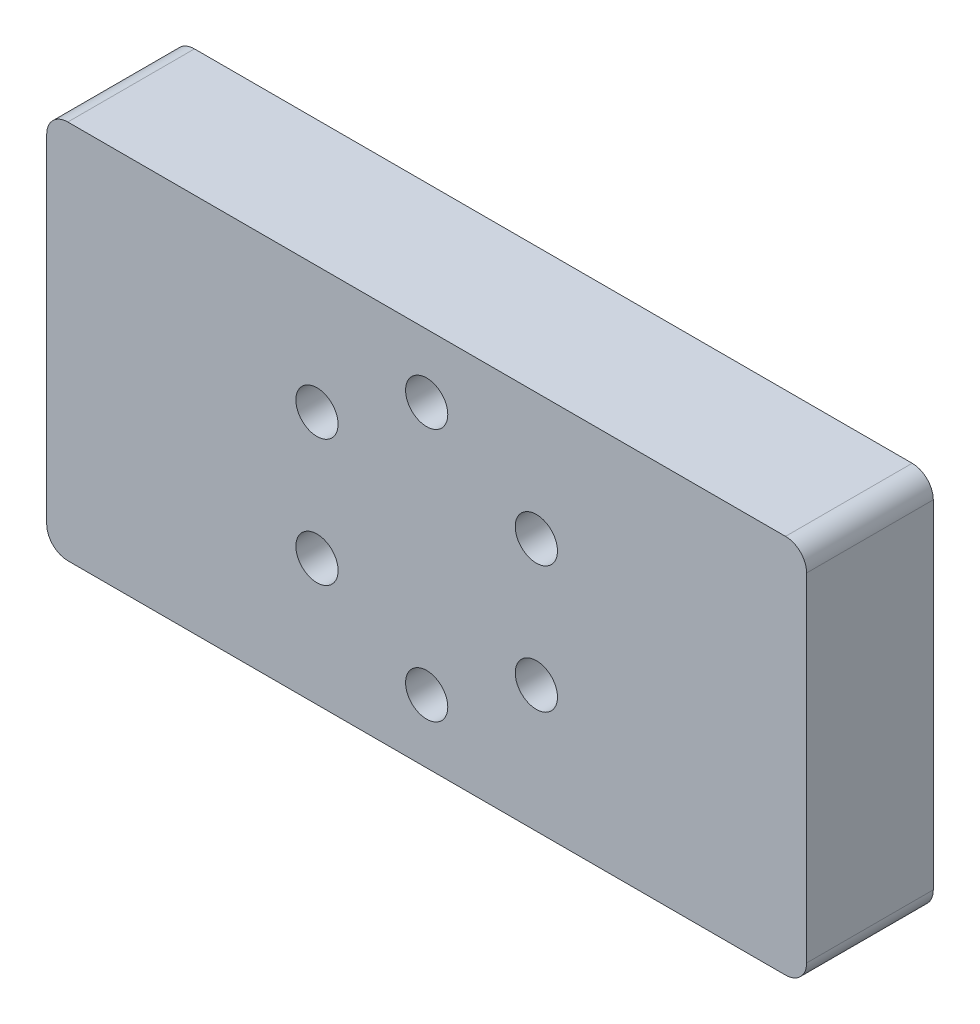
SolidWorks part; units mm, degrees
ref_plane "Plano frontal" through (0, 0, 0) normal (0, 0, 1) x (1, 0, 0)
ref_plane "Plano superior" through (0, 0, 0) normal (0, 1, 0) x (1, 0, 0)
ref_plane "Plano direito" through (0, 0, 0) normal (1, 0, 0) x (0, 0, -1)
sketch "Esboço1" plane through (0, 0, 0) normal (0, 0, 1) x (1, 0, 0)
  line L1 (-85, -45) -> (85, -45)
  line L2 (-90, -40) -> (-90, 40)
  line L3 (-85, 45) -> (85, 45)
  line L4 (90, -40) -> (90, 40)
  line L5 (-90, -45) -> (90, 45) construction
  line L6 (-90, 45) -> (90, -45) construction
  arc A0 (85, 45) -> (90, 40) centre (85, 40) cw
  arc A1 (85, -45) -> (90, -40) centre (85, -40) ccw
  arc A2 (-85, -45) -> (-90, -40) centre (-85, -40) cw
  arc A3 (-90, 40) -> (-85, 45) centre (-85, 40) cw
  point P0 (0, 0)
  dimension "D3" = 5
  dimension "D4" = 5
  dimension "D5" = 5
  dimension "D6" = 5
  dimension "D1" = 180
  dimension "D2" = 90
extrude "Ressalto-extrusão1" add sketch "Esboço1" along normal blind 30
sketch "Esboço2" plane through (0, 0, 30) normal (0, 0, 1) x (1, 0, 0)
  circle A0 centre (0, 30) radius 5
  circle A1 centre (25.9808, 15) radius 5
  circle A2 centre (25.9808, -15) radius 5
  circle A3 centre (0, -30) radius 5
  circle A4 centre (-25.9808, -15) radius 5
  circle A5 centre (-25.9808, 15) radius 5
  point P16 (0, 0)
  dimension "D2" = 10
  dimension "D1" = 30
  dimension "D3" = 6
extrude "Corte-extrusão1" cut sketch "Esboço2" against normal blind 30
